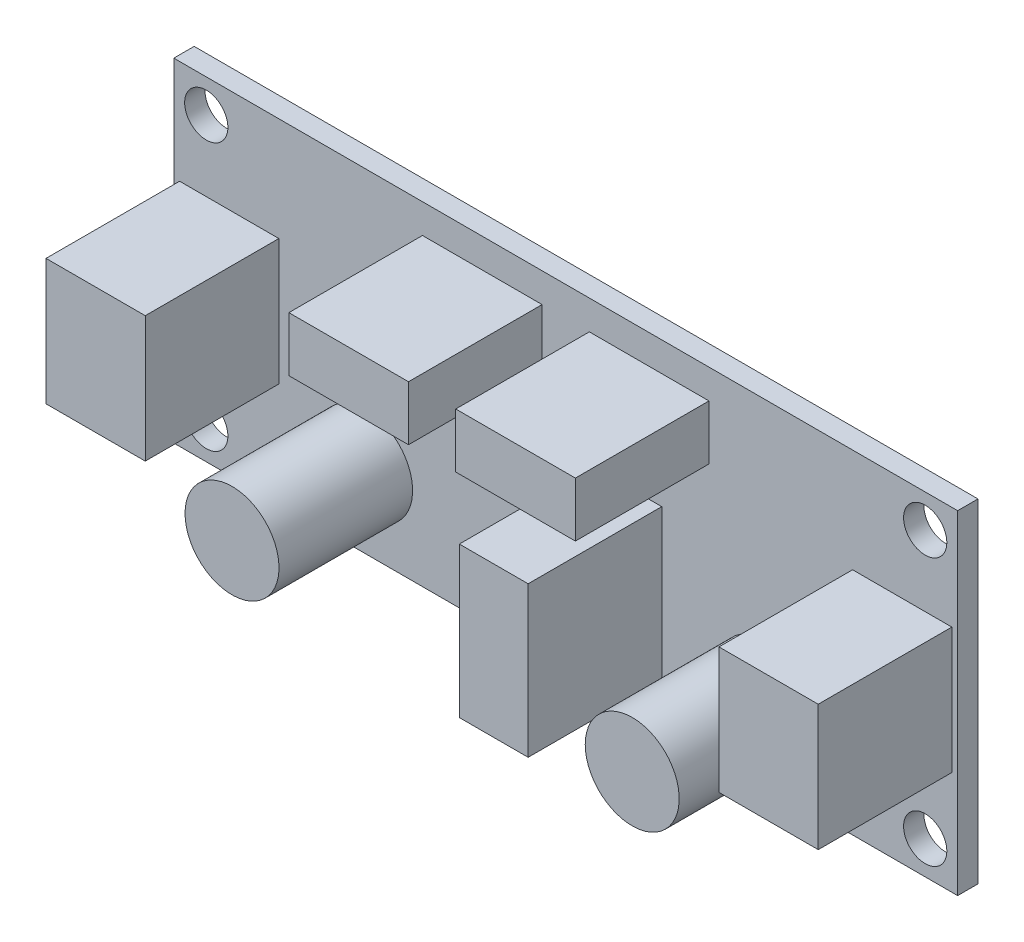
SolidWorks part; units mm, degrees
ref_plane "Plan de face" through (0, 0, 0) normal (0, 0, 1) x (1, 0, 0)
ref_plane "Plan de dessus" through (0, 0, 0) normal (0, 1, 0) x (1, 0, 0)
ref_plane "Plan de droite" through (0, 0, 0) normal (1, 0, 0) x (0, 0, -1)
sketch "Esquisse1" plane through (0, 0, 0) normal (0, 0, 1) x (1, 0, 0)
  line L1 (-30.8, 13.1) -> (30.8, 13.1)
  line L2 (-30.8, 13.1) -> (-30.8, -13.1)
  line L3 (-30.8, -13.1) -> (30.8, -13.1)
  line L4 (30.8, 13.1) -> (30.8, -13.1)
  point P4 (0, 13.1)
  point P6 (-30.8, 0)
  dimension "D1" = 61.6
  dimension "D2" = 26.2
extrude "Boss.-Extru.1" add sketch "Esquisse1" along normal blind 1.6
hole_wizard "Dégagement M31" positions "Esquisse3" profile "Esquisse4" hole size "M3" standard "ISO" end condition through all
sketch "Esquisse3" plane through (0, 0, 1.6) normal (0, 0, 1) x (1, 0, 0)
  line L0 (0, 0) -> (0, 5.8427) construction
  line L2 (0, 0) -> (4.0489, 0) construction
  point P0 (-28.25, 10.5)
  point P12 (28.25, 10.5)
  point P13 (28.25, -10.5)
  point P14 (-28.25, -10.5)
  dimension "D1" = 56.5
  dimension "D2" = 21
sketch "Esquisse4" plane through (-28.25, 10.5, 1.6) normal (1, 0, 0) x (0, -1, 0)
  line L0 (0, 0) -> (0, 1.6)
  line L1 (0, 1.6) -> (1.7, 1.6)
  line L2 (1.7, 1.6) -> (1.7, 0)
  line L5 (1.7, 0) -> (0, 0)
  line L11 (0, -6.35) -> (0, 107.95) construction
  dimension "Diamètre du perçage jusqu'au prochain" = 3.4
  dimension "Profondeur du perçage jusqu'au prochain" = 1.6
sketch "Esquisse5" plane through (0, 0, 1.6) normal (0, 0, 1) x (1, 0, 0)
  line L0 (0, 0) -> (0, 5.7402) construction
  line L1 (-30.3439, 4.95) -> (-22.5439, 4.95)
  line L2 (-30.3439, 4.95) -> (-30.3439, -4.95)
  line L3 (-30.3439, -4.95) -> (-22.5439, -4.95)
  line L4 (-22.5439, 4.95) -> (-22.5439, -4.95)
  line L9 (22.5439, 4.95) -> (22.5439, -4.95)
  line L10 (30.3439, -4.95) -> (22.5439, -4.95)
  line L11 (30.3439, 4.95) -> (30.3439, -4.95)
  line L12 (30.3439, 4.95) -> (22.5439, 4.95)
  line L13 (11.2587, 6.5086) -> (1.856, 6.5086)
  line L22 (2.1402, 1.7485) -> (7.5467, 1.7485)
  line L23 (2.1402, 1.7485) -> (2.1402, -10.0637)
  line L24 (2.1402, -10.0637) -> (7.5467, -10.0637)
  line L25 (7.5467, 1.7485) -> (7.5467, -10.0637)
  line L26 (-11.2587, 10.7986) -> (-1.856, 10.7986)
  line L27 (-11.2587, 10.7986) -> (-11.2587, 6.5086)
  line L28 (-11.2587, 6.5086) -> (-1.856, 6.5086)
  line L29 (-1.856, 10.7986) -> (-1.856, 6.5086)
  line L30 (1.856, 10.7986) -> (1.856, 6.5086)
  line L31 (11.2587, 10.7986) -> (1.856, 10.7986)
  line L32 (11.2587, 10.7986) -> (11.2587, 6.5086)
  circle A0 centre (-15.725, -6.9491) radius 3.6919
  circle A2 centre (15.725, -6.9491) radius 3.6919
  point P4 (-22.5439, 0)
  dimension "D1" = 9.9
  dimension "D2" = 7.8
extrude "Boss.-Extru.2" add sketch "Esquisse5" along normal blind 10.5
